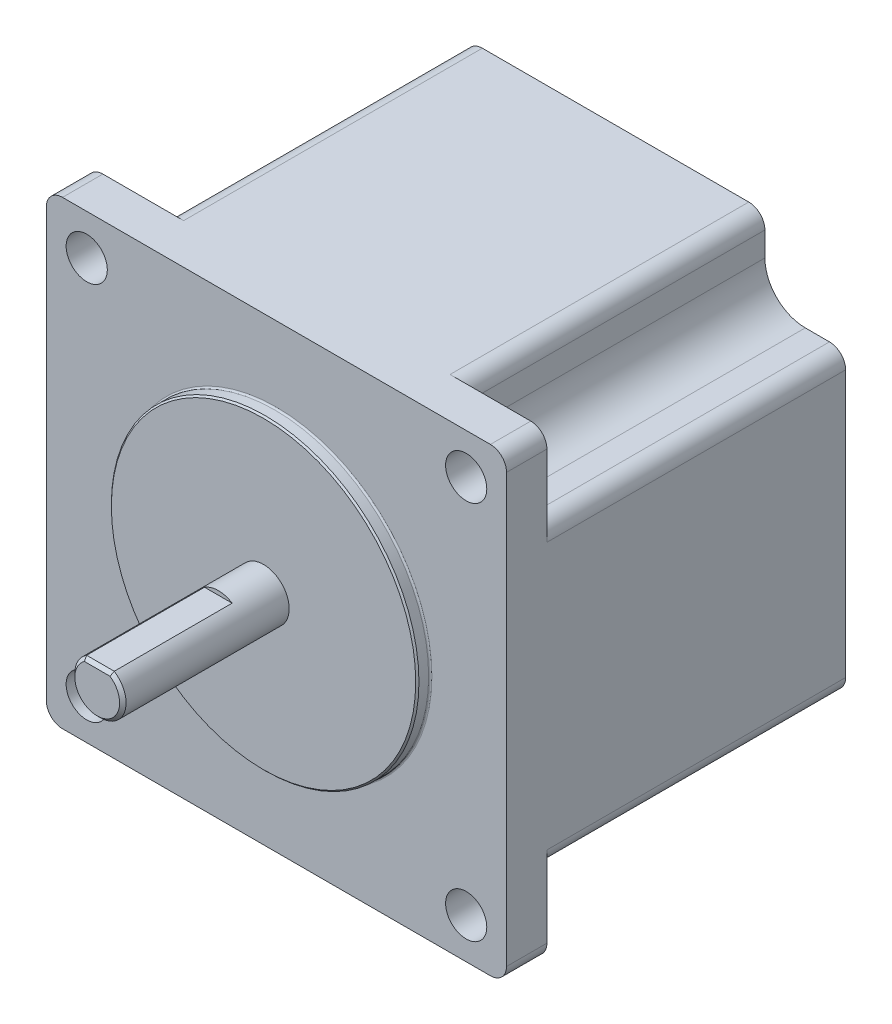
SolidWorks part; units mm, degrees
ref_plane "Plan de face" through (0, 0, 0) normal (0, 0, 1) x (1, 0, 0)
ref_plane "Plan de dessus" through (0, 0, 0) normal (0, 1, 0) x (1, 0, 0)
ref_plane "Plan de droite" through (0, 0, 0) normal (1, 0, 0) x (0, 0, -1)
sketch "Esquisse1" plane through (0, 0, 0) normal (0, 0, 1) x (1, 0, 0)
  line L1 (-26.5, -28.5) -> (26.5, -28.5)
  line L2 (-28.5, -26.5) -> (-28.5, 26.5)
  line L3 (-26.5, 28.5) -> (26.5, 28.5)
  line L4 (28.5, -26.5) -> (28.5, 26.5)
  line L5 (-28.5, -28.5) -> (28.5, 28.5) construction
  line L6 (-28.5, 28.5) -> (28.5, -28.5) construction
  arc A0 (-26.5, -28.5) -> (-28.5, -26.5) centre (-26.5, -26.5) cw
  arc A1 (26.5, -28.5) -> (28.5, -26.5) centre (26.5, -26.5) ccw
  arc A2 (26.5, 28.5) -> (28.5, 26.5) centre (26.5, 26.5) cw
  arc A3 (-28.5, 26.5) -> (-26.5, 28.5) centre (-26.5, 26.5) cw
  point P0 (0, 0)
  dimension "D3" = 2
  dimension "D1" = 57
  dimension "D2" = 57
extrude "Boss.-Extru.1" add sketch "Esquisse1" against normal blind 42
sketch "Esquisse3" plane through (0, 0, 0) normal (0, 0, 1) x (1, 0, 0)
  circle A0 centre (0, 0) radius 19.05
  dimension "D1" = 38.1
extrude "Boss.-Extru.2" add sketch "Esquisse3" along normal blind 1.6
chamfer "Chanfrein1" distance 0.2 angle 45 1 edges at (19.05, 0, 1.6)
fillet "Congé1" radius 0.2 1 edges at (19.05, 0, 0)
sketch "Esquisse4" plane through (0, 0, 1.6) normal (0, 0, 1) x (1, 0, 0)
  circle A0 centre (0, 0) radius 3.175
  dimension "D1" = 6.35
extrude "Boss.-Extru.3" add sketch "Esquisse4" along normal blind 5.6
sketch "Esquisse5" plane through (0, 0, 7.2) normal (0, 0, 1) x (1, 0, 0)
  line L0 (-9.2453, -3.175) -> (7.4611, -3.175) construction
  line L1 (-9.2453, 2.675) -> (7.4611, 2.675) construction
  line L2 (-1.7103, 2.675) -> (1.7103, 2.675)
  arc A0 (-1.7103, 2.675) -> (1.7103, 2.675) centre (0, 0) ccw
  dimension "D1" = 5.85
extrude "Boss.-Extru.4" add sketch "Esquisse5" along normal blind 15
chamfer "Chanfrein2" distance 0.4 angle 45 1 edges at (0, 2.675, 22.2)
sketch "Esquisse6" plane through (0, 0, 0) normal (0, 0, 1) x (1, 0, 0)
  line L0 (0, 28.5) -> (0, -28.5) construction
  line L1 (26.5, 28.5) -> (-26.5, 28.5) construction
  line L2 (-26.5, -28.5) -> (26.5, -28.5) construction
  line L3 (-28.5, 0) -> (28.5, 0) construction
  line L4 (-28.5, 26.5) -> (-28.5, -26.5) construction
  line L5 (28.5, -26.5) -> (28.5, 26.5) construction
  line L6 (-23.5, 23.5) -> (23.5, 23.5)
  line L7 (23.5, -23.5) -> (23.5, 23.5)
  line L8 (-23.5, -23.5) -> (-23.5, 23.5)
  line L9 (-23.5, -23.5) -> (23.5, -23.5)
  circle A0 centre (-23.5, -23.5) radius 2.55
  circle A1 centre (-23.5, 23.5) radius 2.55
  circle A2 centre (23.5, 23.5) radius 2.55
  circle A3 centre (23.5, -23.5) radius 2.55
  point P15 (0, 23.5)
  point P18 (23.5, 0)
  point P21 (-23.5, 0)
  point P24 (0, -23.5)
  dimension "D5" = 5.1
  dimension "D6" = 5.1
  dimension "D7" = 5.1
  dimension "D8" = 5.1
  dimension "D1" = 47
  dimension "D2" = 47
  dimension "D3" = 47
  dimension "D4" = 47
sketch "Esquisse7" plane through (0, 0, -42) normal (0, 0, -1) x (-1, 0, 0)
  line L1 (-23.5, -18.5) -> (-26.5, -18.5)
  line L2 (-18.5, -23.5) -> (-18.5, -26.5)
  line L4 (28.5, -26.5) -> (28.5, 26.5)
  line L5 (26.5, 28.5) -> (-26.5, 28.5)
  line L6 (-28.5, 26.5) -> (-28.5, -26.5)
  line L7 (-26.5, -28.5) -> (26.5, -28.5)
  line L8 (28.5, -16.5) -> (28.5, 16.5)
  line L9 (16.5, 28.5) -> (-16.5, 28.5)
  line L10 (-28.5, 16.5) -> (-28.5, -16.5)
  line L11 (-16.5, -28.5) -> (16.5, -28.5)
  line L13 (-18.5, -18.5) -> (-28.5, -28.5) construction
  line L14 (-18.5, -28.5) -> (-28.5, -18.5) construction
  line L15 (-23.5, 18.5) -> (-26.5, 18.5)
  line L16 (-18.5, 23.5) -> (-18.5, 26.5)
  line L19 (-19.9645, 19.9645) -> (-28.5, 28.5) construction
  line L20 (-18.5, 28.5) -> (-28.5, 18.5) construction
  line L21 (23.5, 18.5) -> (26.5, 18.5)
  line L22 (18.5, 23.5) -> (18.5, 26.5)
  line L25 (19.9645, 19.9645) -> (28.5, 28.5) construction
  line L26 (18.5, 28.5) -> (28.5, 18.5) construction
  line L27 (23.5, -18.5) -> (26.5, -18.5)
  line L28 (18.5, -23.5) -> (18.5, -26.5)
  line L31 (18.5, -18.5) -> (28.5, -28.5) construction
  line L32 (18.5, -28.5) -> (28.5, -18.5) construction
  arc A0 (23.5, -18.5) -> (18.5, -23.5) centre (23.5, -23.5) ccw
  arc A1 (-23.5, -18.5) -> (-18.5, -23.5) centre (-23.5, -23.5) cw
  arc A2 (-23.5, 18.5) -> (-18.5, 23.5) centre (-23.5, 23.5) ccw
  arc A3 (23.5, 18.5) -> (18.5, 23.5) centre (23.5, 23.5) cw
  arc A4 (26.5, -28.5) -> (28.5, -26.5) centre (26.5, -26.5) ccw
  arc A5 (28.5, 26.5) -> (26.5, 28.5) centre (26.5, 26.5) ccw
  arc A6 (-26.5, 28.5) -> (-28.5, 26.5) centre (-26.5, 26.5) ccw
  arc A7 (-28.5, -26.5) -> (-26.5, -28.5) centre (-26.5, -26.5) ccw
  arc A11 (-18.5, -26.5) -> (-16.5, -28.5) centre (-16.5, -26.5) ccw
  arc A12 (18.5, -26.5) -> (16.5, -28.5) centre (16.5, -26.5) cw
  arc A13 (26.5, -18.5) -> (28.5, -16.5) centre (26.5, -16.5) ccw
  arc A14 (26.5, 18.5) -> (28.5, 16.5) centre (26.5, 16.5) cw
  arc A15 (18.5, 26.5) -> (16.5, 28.5) centre (16.5, 26.5) ccw
  arc A16 (-18.5, 26.5) -> (-16.5, 28.5) centre (-16.5, 26.5) cw
  arc A17 (-26.5, 18.5) -> (-28.5, 16.5) centre (-26.5, 16.5) ccw
  arc A18 (-26.5, -18.5) -> (-28.5, -16.5) centre (-26.5, -16.5) cw
  point P0 (-23.5, -23.5)
  point P16 (-23.5, 23.5)
  point P24 (23.5, 23.5)
  point P30 (23.5, -23.5)
  arc M29 (26.5, -28.5) -> (28.5, -26.5) centre (26.5, -26.5) ccw
  line M30 (28.5, -26.5) -> (28.5, 26.5)
  arc M31 (28.5, 26.5) -> (26.5, 28.5) centre (26.5, 26.5) ccw
  line M32 (26.5, 28.5) -> (-26.5, 28.5)
  arc M33 (-26.5, 28.5) -> (-28.5, 26.5) centre (-26.5, 26.5) ccw
  line M34 (-28.5, 26.5) -> (-28.5, -26.5)
  arc M35 (-28.5, -26.5) -> (-26.5, -28.5) centre (-26.5, -26.5) ccw
  line M36 (-26.5, -28.5) -> (26.5, -28.5)
  dimension "D2" = 5
  dimension "D3" = 2
  dimension "D1" = 0
extrude "Enlèv. mat.-Extru.1" cut sketch "Esquisse7" against normal blind 37 contours A17 L15 A2 L16 A16 M32 M33 M34 | A15 L22 A3 L21 A14 M30 M31 M32 | A13 L27 A0 L28 A12 M36 M29 M30 | L1 A18 A11 L2 A1 M34 M35 M36
extrude "Enlèv. mat.-Extru.2" cut sketch "Esquisse6" against normal through all contours L6 A1 L8 | L8 A1 L6 | L7 A2 L6 | L6 A2 L7 | L7 A3 L9 | L9 A3 L7 | L9 A0 L8 | L8 A0 L9
equation "\"D6@Esquisse6\"=\"D5@Esquisse6\""
equation "\"D7@Esquisse6\"=\"D5@Esquisse6\""
equation "\"D8@Esquisse6\"=\"D5@Esquisse6\""
equation "\"D1@Esquisse6\"=\"D3@Esquisse6\""
equation "\"D2@Esquisse6\"=\"D3@Esquisse6\""
equation "\"D4@Esquisse6\"=\"D3@Esquisse6\""
